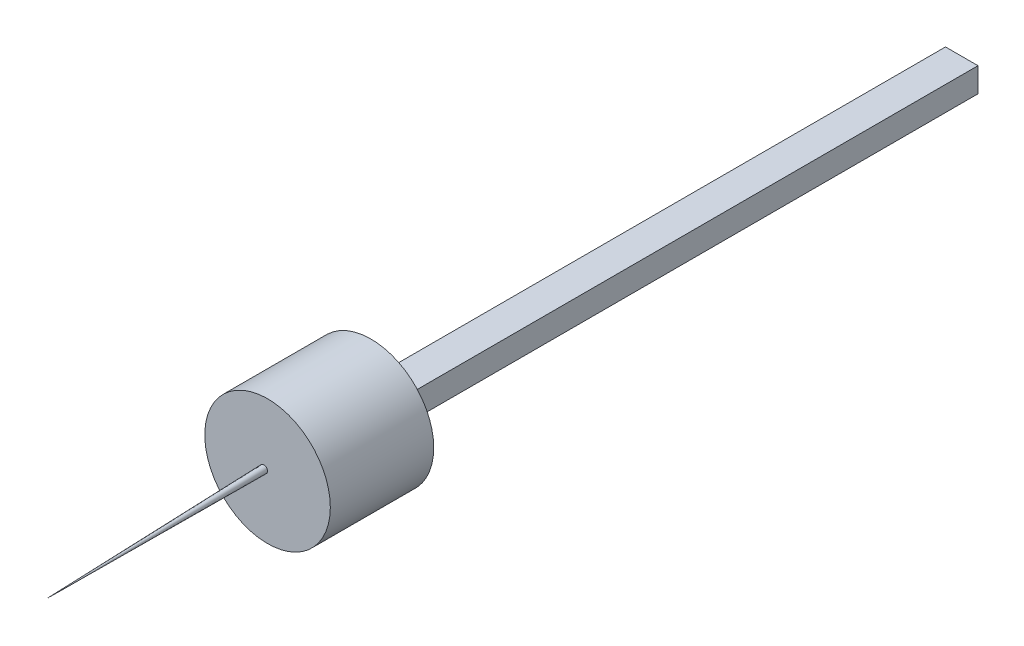
SolidWorks part; units mm, degrees
ref_plane "Front Plane" through (0, 0, 0) normal (0, 0, 1) x (1, 0, 0)
ref_plane "Top Plane" through (0, 0, 0) normal (0, 1, 0) x (1, 0, 0)
ref_plane "Right Plane" through (0, 0, 0) normal (1, 0, 0) x (0, 0, -1)
sketch "Sketch1" plane through (0, 0, 0) normal (0, 0, 1) x (1, 0, 0)
  line L1 (-2.2, -1.65) -> (2.2, -1.65)
  line L2 (-2.2, -1.65) -> (-2.2, 1.65)
  line L3 (-2.2, 1.65) -> (2.2, 1.65)
  line L4 (2.2, -1.65) -> (2.2, 1.65)
  line L5 (-2.2, -1.65) -> (2.2, 1.65) construction
  line L6 (-2.2, 1.65) -> (2.2, -1.65) construction
  point P0 (0, 0)
  dimension "D1" = 4.4
  dimension "D2" = 3.3
extrude "Boss-Extrude1" add sketch "Sketch1" along normal blind 80
sketch "Sketch2" plane through (0, 0, 80) normal (0, 0, 1) x (1, 0, 0)
  circle A0 centre (0, 0) radius 8.5
  dimension "D1" = 17
extrude "Boss-Extrude2" add sketch "Sketch2" along normal blind 14
sketch "Sketch3" plane through (0, 0, 0) normal (0, 1, 0) x (1, 0, 0)
  line L0 (0, -94) -> (0, -124)
  line L1 (-8.5, -94) -> (8.5, -94) construction
  line L2 (0, -124) -> (-0.5, -94)
  line L3 (-0.5, -94) -> (0, -94)
  dimension "D1" = 0.5
  dimension "D2" = 30
revolve "Revolve1" add sketch "Sketch3" angle 360 about L2
